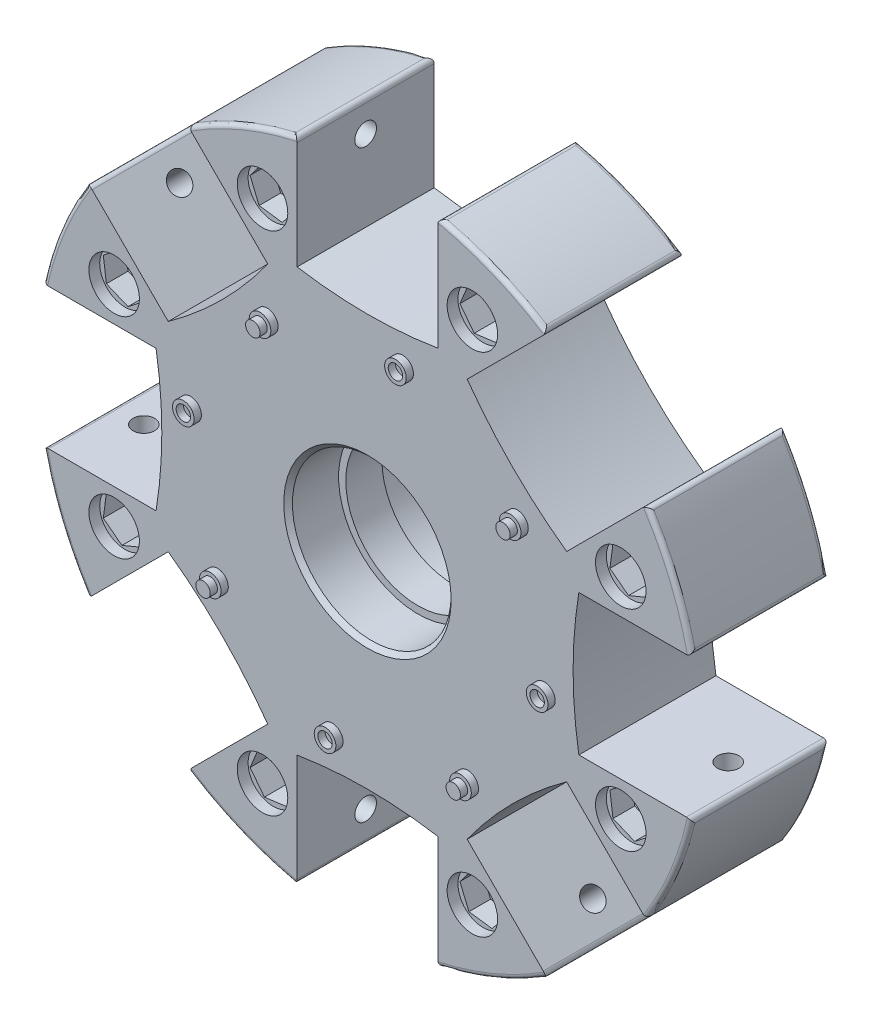
SolidWorks part; units mm, degrees
ref_plane "Front Plane" through (0, 0, 0) normal (0, 0, 1) x (1, 0, 0)
ref_plane "Top Plane" through (0, 0, 0) normal (0, 1, 0) x (1, 0, 0)
ref_plane "Right Plane" through (0, 0, 0) normal (1, 0, 0) x (0, 0, -1)
sketch "Sketch2" plane through (0, 0, 0) normal (0, 0, 1) x (1, 0, 0)
  line L0 (-9.75, 44.9548) -> (-9.75, 29.2975)
  line L1 (0, 0) -> (0, 56.2048) construction
  line L2 (9.75, 44.9548) -> (9.75, 29.2975)
  line L3 (24.8936, 38.6822) -> (13.8222, 27.6107)
  line L4 (38.6822, 24.8936) -> (27.6107, 13.8222)
  line L5 (44.9548, 9.75) -> (29.2975, 9.75)
  line L6 (44.9548, -9.75) -> (29.2975, -9.75)
  line L7 (38.6822, -24.8936) -> (27.6107, -13.8222)
  line L8 (24.8936, -38.6822) -> (13.8222, -27.6107)
  line L9 (9.75, -44.9548) -> (9.75, -29.2975)
  line L10 (-9.75, -44.9548) -> (-9.75, -29.2975)
  line L11 (-24.8936, -38.6822) -> (-13.8222, -27.6107)
  line L12 (-38.6822, -24.8936) -> (-27.6107, -13.8222)
  line L13 (-44.9548, -9.75) -> (-29.2975, -9.75)
  line L14 (-44.9548, 9.75) -> (-29.2975, 9.75)
  line L15 (-38.6822, 24.8936) -> (-27.6107, 13.8222)
  line L16 (-24.8936, 38.6822) -> (-13.8222, 27.6107)
  line L17 (0, 0) -> (14.542, 35.1074) construction
  arc A0 (-38.6822, 24.8936) -> (-44.9548, 9.75) centre (0, 0) ccw
  circle A1 centre (0, 0) radius 10
  circle A2 centre (0, 0) radius 38 construction
  circle A3 centre (0, 0) radius 50 construction
  arc A4 (-9.75, 29.2975) -> (9.75, 29.2975) centre (0, 88.5) ccw
  arc A5 (13.8222, 27.6107) -> (27.6107, 13.8222) centre (62.579, 62.579) ccw
  circle A6 centre (0, 0) radius 10
  arc A7 (29.2975, 9.75) -> (29.2975, -9.75) centre (88.5, 0) ccw
  circle A8 centre (0, 0) radius 10
  arc A9 (27.6107, -13.8222) -> (13.8222, -27.6107) centre (62.579, -62.579) ccw
  circle A10 centre (0, 0) radius 10
  arc A11 (9.75, -29.2975) -> (-9.75, -29.2975) centre (0, -88.5) ccw
  circle A12 centre (0, 0) radius 10
  arc A13 (-13.8222, -27.6107) -> (-27.6107, -13.8222) centre (-62.579, -62.579) ccw
  circle A14 centre (0, 0) radius 10
  arc A15 (-29.2975, -9.75) -> (-29.2975, 9.75) centre (-88.5, 0) ccw
  circle A16 centre (0, 0) radius 10
  arc A17 (-27.6107, 13.8222) -> (-13.8222, 27.6107) centre (-62.579, 62.579) ccw
  circle A18 centre (0, 0) radius 10
  circle A19 centre (14.542, 35.1074) radius 1.75
  arc A20 (-9.75, 44.9548) -> (-24.8936, 38.6822) centre (0, 0) ccw
  arc A21 (24.8936, 38.6822) -> (9.75, 44.9548) centre (0, 0) ccw
  arc A22 (44.9548, 9.75) -> (38.6822, 24.8936) centre (0, 0) ccw
  arc A23 (38.6822, -24.8936) -> (44.9548, -9.75) centre (0, 0) ccw
  arc A24 (9.75, -44.9548) -> (24.8936, -38.6822) centre (0, 0) ccw
  arc A25 (-24.8936, -38.6822) -> (-9.75, -44.9548) centre (0, 0) ccw
  arc A26 (-44.9548, -9.75) -> (-38.6822, -24.8936) centre (0, 0) ccw
  circle A27 centre (35.1074, 14.542) radius 1.75
  circle A28 centre (0, 0) radius 10
  circle A29 centre (35.1074, -14.542) radius 1.75
  circle A30 centre (0, 0) radius 10
  circle A31 centre (14.542, -35.1074) radius 1.75
  circle A32 centre (0, 0) radius 10
  circle A33 centre (-14.542, -35.1074) radius 1.75
  circle A34 centre (0, 0) radius 10
  circle A35 centre (-35.1074, -14.542) radius 1.75
  circle A36 centre (0, 0) radius 10
  circle A37 centre (-35.1074, 14.542) radius 1.75
  circle A38 centre (0, 0) radius 10
  circle A39 centre (-14.542, 35.1074) radius 1.75
  circle A40 centre (0, 0) radius 10
  circle A41 centre (0, 0) radius 40.5 construction
  point P56 (0, 0)
  point P57 (0, 28.5)
  point P80 (0, 0)
  point P81 (0, 40.5)
  dimension "D2" = 20
  dimension "D3" = 76
  dimension "D4" = 19.5
  dimension "D5" = 100
  dimension "D6" = 60
  dimension "D9" = 3.5
  dimension "D12" = 46
  dimension "D13" = 81
  dimension "D7" = 12
  dimension "D8" = 8
  dimension "D10" = 22.5
  dimension "D11" = 8
extrude "Boss-Extrude1" add sketch "Sketch2" along normal mid plane 19 contours L13 A26 L12 A13 L11 A25 L10 A11 L9 A24 L8 A9 L7 A23 L6 A7 L5 A22 L4 A5 L3 A21 L2 A4 L0 A20 L16 A17 L15 A0 L14 A15 A39 A37 A35 A33 A31 A29 A27 A1 A19
fillet "Fillet2" radius 0.6 32 edges at (-24.8936, -38.6822, 0) (-17.6034, -42.4985, 9.5) (-9.75, -44.9548, 0) (-17.6034, -42.4985, -9.5) (-44.9548, -9.75, 0) (-42.4985, -17.6034, 9.5) (-38.6822, -24.8936, 0) (-42.4985, -17.6034, -9.5) (-38.6822, 24.8936, 0) (-42.4985, 17.6034, 9.5) (-44.9548, 9.75, 0) (-42.4985, 17.6034, -9.5) (-9.75, 44.9548, 0) (-17.6034, 42.4985, 9.5) (-24.8936, 38.6822, 0) (-17.6034, 42.4985, -9.5) (24.8936, 38.6822, 0) (17.6034, 42.4985, 9.5) (9.75, 44.9548, 0) (17.6034, 42.4985, -9.5) (9.75, -44.9548, 0) (17.6034, -42.4985, 9.5) (24.8936, -38.6822, 0) (17.6034, -42.4985, -9.5) (38.6822, -24.8936, 0) (42.4985, -17.6034, 9.5) (44.9548, -9.75, 0) (42.4985, -17.6034, -9.5) (44.9548, 9.75, 0) (42.4985, 17.6034, 9.5) (38.6822, 24.8936, 0) (42.4985, 17.6034, -9.5)
sketch "Sketch3" plane through (0, 0, 9.5) normal (0, 0, 1) x (1, 0, 0)
  circle A0 centre (0, 0) radius 11
extrude "Cut-Extrude1" cut sketch "Sketch3" against normal blind 7
mirror "Mirror1" about plane through (0, 0, 0) normal (0, 0, 1) of "Cut-Extrude1"
chamfer "Chamfer1" distance 0.6 angle 45 2 edges at (11, 0, 9.5) (11, 0, -9.5)
sketch "Sketch4" plane through (0, 0, -9.5) normal (0, 0, -1) x (-1, 0, 0)
  line L0 (-14.542, 35.1074) -> (0, 0) construction
  line L1 (-13.2982, 32.1048) -> (-11.3198, 34.6832)
  line L2 (-11.3198, 34.6832) -> (-12.5635, 37.6858)
  line L3 (-12.5635, 37.6858) -> (-15.7857, 38.11)
  line L4 (-15.7857, 38.11) -> (-17.7642, 35.5316)
  line L5 (-17.7642, 35.5316) -> (-16.5204, 32.529)
  line L6 (-16.5204, 32.529) -> (-13.2982, 32.1048)
  circle A0 centre (-14.542, 35.1074) radius 2.8146 construction
  dimension "D1" = 6.5
extrude "Cut-Extrude2" cut sketch "Sketch4" against normal blind 3 from offset 1.5 offset against normal yes
sketch "Sketch7" plane through (0, 0, 0) normal (1, 0, 0) x (0, 0, -1)
  circle A0 centre (0, 40.5) radius 1.5
  dimension "D1" = 3
extrude "Cut-Extrude4" cut sketch "Sketch7" against normal mid plane 30
pattern_circular "CirPattern2" count 8 over 360 about axis through (0, 0, 0) along (0, 0, 1) of "Cut-Extrude4"
sketch "Sketch8" plane through (0, 0, -9.5) normal (0, 0, -1) x (-1, 0, 0)
  circle A0 centre (-14.542, 35.1074) radius 3.5
  dimension "D1" = 7
extrude "Cut-Extrude5" cut sketch "Sketch8" against normal blind 1.5
mirror "Mirror2" about plane through (0, 0, 0) normal (0, 0, 1) of "Cut-Extrude2", "Cut-Extrude5"
pattern_circular "CirPattern3" count 8 over 360 about axis through (0, 0, 0) along (0, 0, 1) of "Mirror2", "Cut-Extrude2", "Cut-Extrude5"
sketch "Sketch9" plane through (0, 0, -9.5) normal (0, 0, -1) x (-1, 0, 0)
  line L0 (0, 0) -> (0, 36.406) construction
  line L1 (-4.8773, 24.5196) -> (0, 0) construction
  line L2 (-4.8773, 24.5196) -> (-20.7867, 13.8893) construction
  line L3 (-20.7867, 13.8893) -> (-24.5196, -4.8773) construction
  line L4 (-24.5196, -4.8773) -> (-13.8893, -20.7867) construction
  line L5 (-13.8893, -20.7867) -> (4.8773, -24.5196) construction
  line L6 (4.8773, -24.5196) -> (20.7867, -13.8893) construction
  line L7 (20.7867, -13.8893) -> (24.5196, 4.8773) construction
  line L8 (24.5196, 4.8773) -> (13.8893, 20.7867) construction
  line L9 (13.8893, 20.7867) -> (-4.8773, 24.5196) construction
  circle A0 centre (13.8893, 20.7867) radius 1.5
  circle A1 centre (-4.8773, 24.5196) radius 1.5
  circle A2 centre (0, 0) radius 23.097 construction
  circle A3 centre (24.5196, 4.8773) radius 1.5
  circle A4 centre (20.7867, -13.8893) radius 1.5
  circle A5 centre (4.8773, -24.5196) radius 1.5
  circle A6 centre (-13.8893, -20.7867) radius 1.5
  circle A7 centre (-24.5196, -4.8773) radius 1.5
  circle A8 centre (-20.7867, 13.8893) radius 1.5
  point P30 (0, 0)
  dimension "D1" = 3
  dimension "D2" = 25
  dimension "D4" = 8
  dimension "D3" = 11.25
extrude "Boss-Extrude2" add sketch "Sketch9" along normal blind 1 contours A1 | A7 | A8 | A0 | A3 | A4 | A5 | A6
mirror "Mirror5" about plane through (0, 0, 0) normal (0, 0, 1) of "Boss-Extrude2"
sketch "Sketch11" plane through (0, 0, 10.5) normal (0, 0, 1) x (1, 0, 0)
  circle A0 centre (20.7867, 13.8893) radius 1
  dimension "D1" = 2
extrude "Boss-Extrude4" add sketch "Sketch11" along normal blind 1
sketch "Sketch12" plane through (0, 0, 10.5) normal (0, 0, 1) x (1, 0, 0)
  circle A0 centre (24.5196, -4.8773) radius 1
  dimension "D1" = 2
extrude "Cut-Extrude8" cut sketch "Sketch12" against normal blind 1
pattern_circular "CirPattern9" count 4 over 360 about axis through (0, 0, 0) along (0, 0, 1) of "Boss-Extrude4", "Cut-Extrude8"
mirror "Mirror6" about plane through (0, 0, 0) normal (0, 0, 1) of "CirPattern9", "Boss-Extrude4", "Cut-Extrude8"
